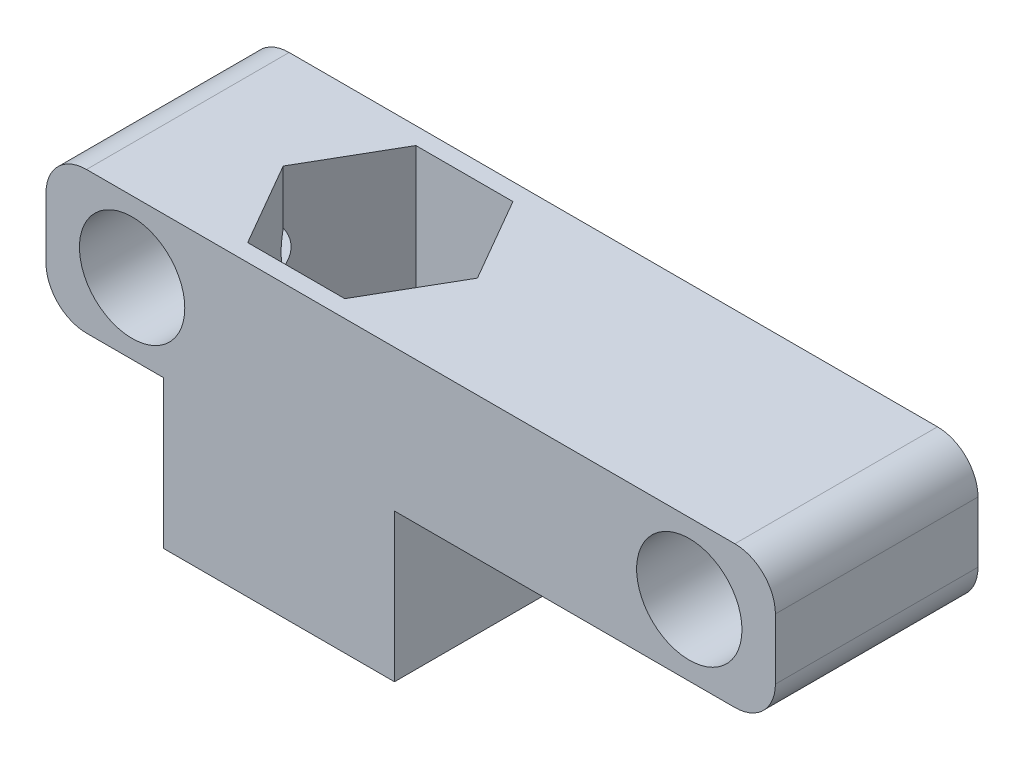
SolidWorks part; units mm, degrees
ref_plane "Alzado" through (0, 0, 0) normal (0, 0, 1) x (1, 0, 0)
ref_plane "Planta" through (0, 0, 0) normal (0, 1, 0) x (1, 0, 0)
ref_plane "Vista lateral" through (0, 0, 0) normal (1, 0, 0) x (0, 0, -1)
sketch "Croquis1" plane through (0, 0, 0) normal (0, 0, 1) x (1, 0, 0)
  line L1 (-46.0167, 15.878) -> (-10.0167, 15.878)
  line L2 (-46.0167, 15.878) -> (-46.0167, 8.878)
  line L3 (-46.0167, 8.878) -> (-10.0167, 8.878)
  line L4 (-10.0167, 15.878) -> (-10.0167, 8.878)
  circle A0 centre (-41.7667, 12.378) radius 2.6
  circle A1 centre (-14.2667, 12.378) radius 2.6
  dimension "D5" = 2
  dimension "D6" = 4.25
  dimension "D1" = 36
  dimension "D2" = 7
  dimension "D3" = 4.25
  dimension "D4" = 3.5
extrude "Saliente-Extruir1" add sketch "Croquis1" along normal blind 10
sketch "Croquis2" plane through (0, 8.878, 0) normal (0, -1, 0) x (1, 0, 0)
  line L0 (-46.0167, 10) -> (-10.0167, 10) construction
  line L1 (-46.0167, 10) -> (-46.0167, 0) construction
  line L3 (-29.7247, 5) -> (-32.1207, 9.15)
  line L4 (-32.1207, 9.15) -> (-36.9127, 9.15)
  line L5 (-36.9127, 9.15) -> (-39.3087, 5)
  line L6 (-39.3087, 5) -> (-36.9127, 0.85)
  line L7 (-36.9127, 0.85) -> (-32.1207, 0.85)
  line L8 (-32.1207, 0.85) -> (-29.7247, 5)
  circle A1 centre (-34.5167, 5) radius 4.15 construction
  dimension "D1" = 5
  dimension "D3" = 8.3
  dimension "D2" = 11.5
extrude "Cortar-Extruir1" cut sketch "Croquis2" against normal up to vertex (7 mm away)
sketch "Croquis4" plane through (0, 8.878, 0) normal (0, -1, 0) x (1, 0, 0)
  line L0 (-39.3087, 5) -> (-40.3087, 5) construction
  line L1 (-29.7247, 5) -> (-32.1207, 9.15)
  line L2 (-32.1207, 9.15) -> (-36.9127, 9.15)
  line L3 (-36.9127, 9.15) -> (-39.3087, 5)
  line L4 (-39.3087, 5) -> (-36.9127, 0.85)
  line L5 (-36.9127, 0.85) -> (-32.1207, 0.85)
  line L6 (-32.1207, 0.85) -> (-29.7247, 5)
  line L7 (-46.0167, 10) -> (-10.0167, 10) construction
  line L8 (-40.2167, 10) -> (-28.8167, 10)
  line L9 (-40.2167, 10) -> (-40.2167, 0)
  line L10 (-40.2167, 0) -> (-28.8167, 0)
  line L11 (-28.8167, 10) -> (-28.8167, 0)
  line L12 (-46.0167, 0) -> (-10.0167, 0) construction
  circle A1 centre (-34.5167, 5) radius 4.15 construction
  dimension "D1" = 11.4
  dimension "D2" = 8.3
extrude "Saliente-Extruir2" add sketch "Croquis4" along normal blind 5
fillet "Redondeo1" radius 2 4 edges at (-10.0167, 15.878, 5) (-10.0167, 8.878, 5) (-46.0167, 8.878, 5) (-46.0167, 15.878, 5)
sketch "Croquis5" plane through (0, 3.878, 0) normal (0, -1, 0) x (1, 0, 0)
  line L0 (-40.2167, 0) -> (-28.8167, 10) construction
  line L1 (-40.2167, 10) -> (-28.8167, 10)
  line L2 (-40.2167, 10) -> (-40.2167, 0)
  line L3 (-40.2167, 0) -> (-28.8167, 0)
  line L4 (-28.8167, 10) -> (-28.8167, 0)
  circle A0 centre (-34.5167, 5) radius 3.25
extrude "Saliente-Extruir3" add sketch "Croquis5" along normal blind 2.3
